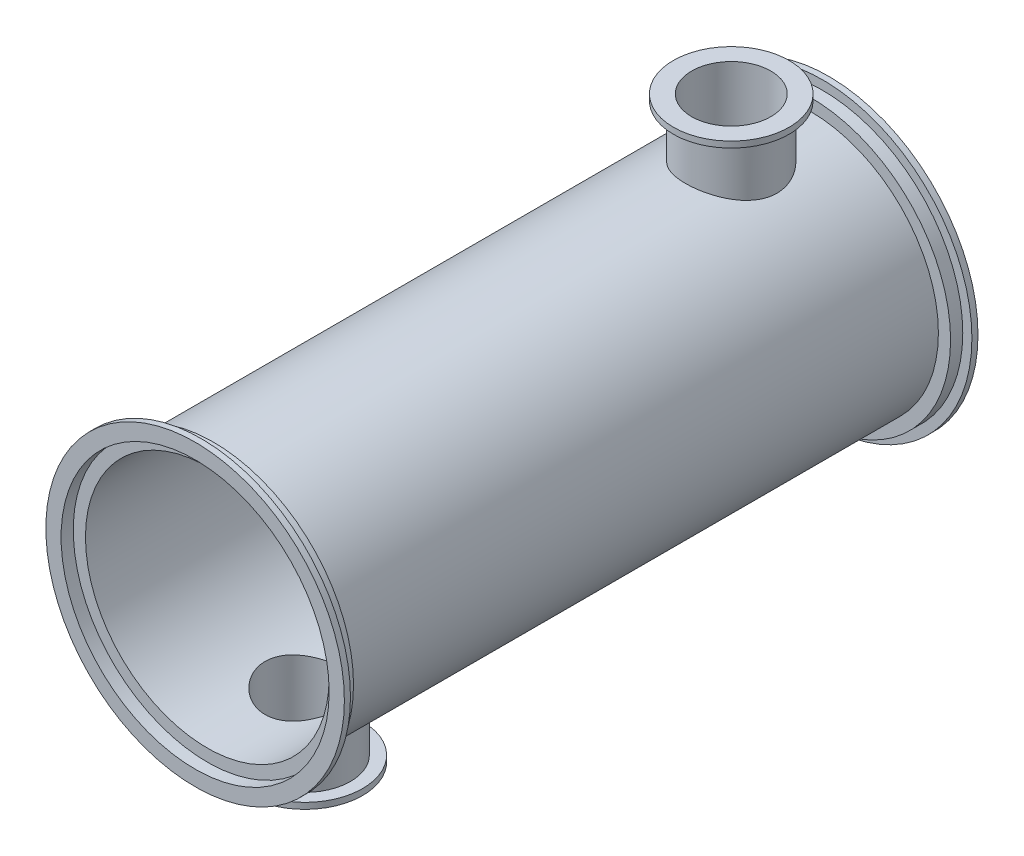
SolidWorks part; units mm, degrees
ref_plane "Front Plane" through (0, 0, 0) normal (0, 0, 1) x (1, 0, 0)
ref_plane "Top Plane" through (0, 0, 0) normal (0, 1, 0) x (1, 0, 0)
ref_plane "Right Plane" through (0, 0, 0) normal (1, 0, 0) x (0, 0, -1)
sketch "Sketch1" plane through (0, 0, 0) normal (1, 0, 0) x (0, 0, -1)
  line L0 (0, 0) -> (0, 509.4877) construction
  line L1 (-500, 0) -> (500, 0) construction
  line L2 (500, 200) -> (-500, 200)
  line L3 (500, 200) -> (500, 220)
  line L4 (500, 220) -> (520, 220)
  line L5 (520, 220) -> (520, 245)
  line L6 (520, 245) -> (510, 245)
  line L7 (510, 245) -> (510, 230)
  line L8 (510, 230) -> (490, 230)
  line L9 (490, 230) -> (490, 210)
  line L10 (490, 210) -> (-490, 210)
  line L11 (-490, 230) -> (-490, 210)
  line L12 (-510, 230) -> (-490, 230)
  line L13 (-510, 245) -> (-510, 230)
  line L14 (-520, 245) -> (-510, 245)
  line L15 (-520, 220) -> (-520, 245)
  line L16 (-500, 220) -> (-520, 220)
  line L17 (-500, 200) -> (-500, 220)
  point P17 (0, 210)
  point P24 (0, 200)
  dimension "D1" = 500
  dimension "D2" = 200
  dimension "D3" = 220
  dimension "D4" = 10
  dimension "D5" = 10
  dimension "D6" = 25
  dimension "D7" = 20
  dimension "D8" = 10
  dimension "D9" = 10
revolve "Revolve1" add sketch "Sketch1" angle 360 about L1
sketch "Sketch3" plane through (0, 0, 0) normal (0, 1, 0) x (1, 0, 0)
  line L0 (0, 510) -> (0, 360) construction
  line L1 (-230, 510) -> (230, 510) construction
  circle A0 centre (0, 360) radius 75
  circle A1 centre (0, 360) radius 65
  dimension "D2" = 150
  dimension "D1" = 150
  dimension "D3" = 10
extrude "Boss-Extrude4" add sketch "Sketch3" against normal up to surface (90 mm away) from offset 300
sketch "Sketch4" plane through (0, 300, 0) normal (0, 1, 0) x (1, 0, 0)
  circle A0 centre (0, 360) radius 65 construction
  circle A1 centre (0, 360) radius 65
extrude "Cut-Extrude2" cut sketch "Sketch4" against normal up to surface (100 mm away)
sketch "Sketch6" plane through (0, 300, 0) normal (0, 1, 0) x (1, 0, 0)
  circle A0 centre (0, 360) radius 65 construction
  circle A1 centre (0, 360) radius 65
  circle A4 centre (0, 360) radius 95
  circle A5 centre (0, 360) radius 95
  dimension "D1" = 20
extrude "Boss-Extrude5" add sketch "Sketch6" against normal blind 10
ref_plane "Plane4" through (0, -300, 0) normal (0, 1, 0) x (1, 0, 0)
sketch "Sketch8" plane through (0, -300, 0) normal (0, 1, 0) x (1, 0, 0)
  line L0 (230, -490) -> (-230, -490) construction
  line L1 (210, -490) -> (210, 490) construction
  circle A0 centre (0, -340) radius 75
  circle A1 centre (0, -340) radius 65
  dimension "D2" = 150
  dimension "D1" = 150
  dimension "D3" = 210
  dimension "D4" = 10
extrude "Boss-Extrude7" add sketch "Sketch8" along normal up to surface (90 mm away)
sketch "Sketch9" plane through (0, -300, 0) normal (0, -1, 0) x (1, 0, 0)
  circle A0 centre (0, 340) radius 65 construction
  circle A1 centre (0, 340) radius 65
extrude "Cut-Extrude3" cut sketch "Sketch9" against normal up to surface (100 mm away)
sketch "Sketch10" plane through (0, -300, 0) normal (0, -1, 0) x (1, 0, 0)
  circle A0 centre (0, 340) radius 95
  circle A1 centre (0, 340) radius 75
  circle A2 centre (0, 340) radius 75
  dimension "D1" = 0
  dimension "D2" = 20
extrude "Boss-Extrude8" add sketch "Sketch10" against normal blind 10
ref_plane "Plane6" through (0, -450, 0) normal (0, -1, 0) x (-1, 0, 0)
